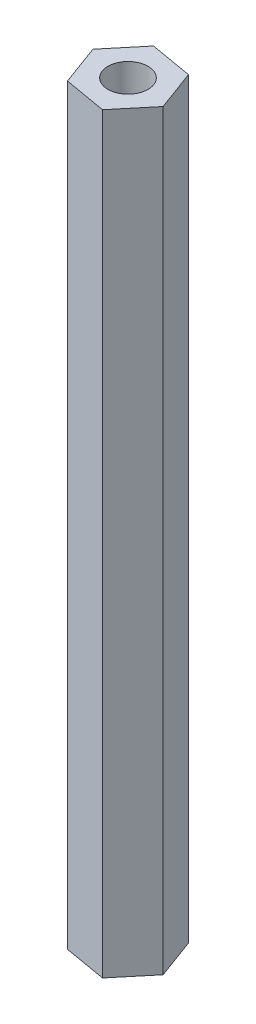
SolidWorks part; units mm, degrees
ref_plane "Front Plane" through (0, 0, 0) normal (0, 0, 1) x (1, 0, 0)
ref_plane "Top Plane" through (0, 0, 0) normal (0, 1, 0) x (1, 0, 0)
ref_plane "Right Plane" through (0, 0, 0) normal (1, 0, 0) x (0, 0, -1)
sketch "Sketch1" plane through (0, 0, 0) normal (0, 1, 0) x (1, 0, 0)
  line L0 (1.0373, -2.815) -> (2.9565, -0.5091)
  line L1 (2.9565, -0.5091) -> (1.9192, 2.3058)
  line L2 (1.9192, 2.3058) -> (-1.0373, 2.815)
  line L3 (-1.0373, 2.815) -> (-2.9565, 0.5091)
  line L4 (-2.9565, 0.5091) -> (-1.9192, -2.3058)
  line L5 (-1.9192, -2.3058) -> (1.0373, -2.815)
  circle A0 centre (0, 0) radius 1.4
extrude "Boss-Extrude1" add sketch "Sketch1" along normal blind 52.5
